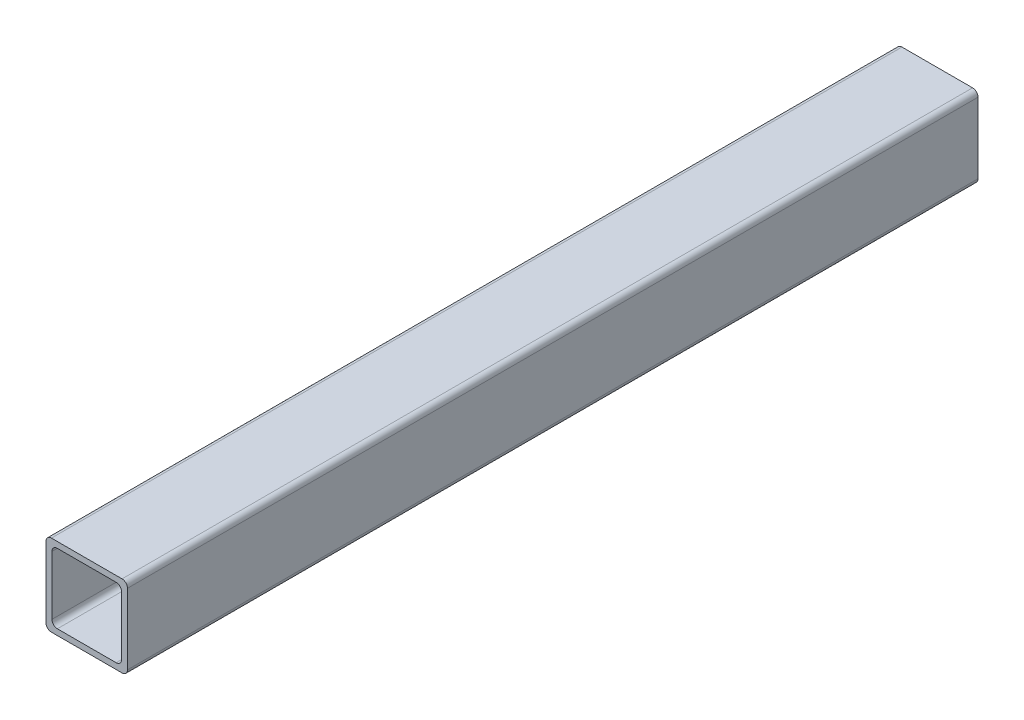
SolidWorks part; units mm, degrees
material "ASTM A500 Grade B Steel"
ref_plane "Front Plane" through (0, 0, 0) normal (0, 0, 1) x (1, 0, 0)
ref_plane "Top Plane" through (0, 0, 0) normal (0, 1, 0) x (1, 0, 0)
ref_plane "Right Plane" through (0, 0, 0) normal (1, 0, 0) x (0, 0, -1)
sketch "Sketch1" plane through (0, 0, 0) normal (0, 0, 1) x (1, 0, 0)
  line L0 (5.3086, -2.7686) -> (32.7914, -2.7686)
  line L1 (2.54, 0) -> (35.56, 0)
  line L2 (0, -2.54) -> (0, -35.56)
  line L3 (2.54, -38.1) -> (35.56, -38.1)
  line L4 (38.1, -2.54) -> (38.1, -35.56)
  line L5 (35.3314, -5.3086) -> (35.3314, -32.7914)
  line L6 (5.3086, -35.3314) -> (32.7914, -35.3314)
  line L7 (2.7686, -5.3086) -> (2.7686, -32.7914)
  line L8 (0, 0) -> (0, -38.1) construction
  line L9 (0, -38.1) -> (38.1, -38.1) construction
  line L10 (38.1, 0) -> (38.1, -38.1) construction
  line L11 (2.7686, -2.7686) -> (2.7686, -35.3314) construction
  line L12 (2.7686, -35.3314) -> (35.3314, -35.3314) construction
  line L13 (35.3314, -2.7686) -> (35.3314, -35.3314) construction
  line L14 (2.7686, -2.7686) -> (35.3314, -2.7686) construction
  line L15 (0, 0) -> (38.1, 0) construction
  arc A0 (0, -35.56) -> (2.54, -38.1) centre (2.54, -35.56) ccw
  arc A1 (38.1, -35.56) -> (35.56, -38.1) centre (35.56, -35.56) cw
  arc A2 (2.7686, -32.7914) -> (5.3086, -35.3314) centre (5.3086, -32.7914) ccw
  arc A3 (32.7914, -35.3314) -> (35.3314, -32.7914) centre (32.7914, -32.7914) ccw
  arc A4 (35.3314, -5.3086) -> (32.7914, -2.7686) centre (32.7914, -5.3086) ccw
  arc A5 (38.1, -2.54) -> (35.56, 0) centre (35.56, -2.54) ccw
  arc A6 (0, -2.54) -> (2.54, 0) centre (2.54, -2.54) cw
  arc A7 (5.3086, -2.7686) -> (2.7686, -5.3086) centre (5.3086, -5.3086) ccw
  point P12 (0, -38.1)
  dimension "D4" = 2.54
  dimension "D3" = 2.7686
extrude "Boss-Extrude1" add sketch "Sketch1" along normal blind 397
sketch "Sketch2" plane through (0, 0, 0) normal (0, 0, -1) x (-1, 0, 0)
  line L4 (0, -35.56) -> (0, -2.54)
  line L5 (-2.54, 0) -> (-35.56, 0)
  line L6 (-38.1, -2.54) -> (-38.1, -35.56)
  line L7 (-35.56, -38.1) -> (-2.54, -38.1)
  line L8 (0, -35.56) -> (0, -2.54)
  line L9 (-2.54, 0) -> (-35.56, 0)
  line L10 (-38.1, -2.54) -> (-38.1, -35.56)
  line L11 (-35.56, -38.1) -> (-2.54, -38.1)
  arc A4 (-2.54, -38.1) -> (0, -35.56) centre (-2.54, -35.56) ccw
  arc A5 (0, -2.54) -> (-2.54, 0) centre (-2.54, -2.54) ccw
  arc A6 (-35.56, 0) -> (-38.1, -2.54) centre (-35.56, -2.54) ccw
  arc A7 (-38.1, -35.56) -> (-35.56, -38.1) centre (-35.56, -35.56) ccw
  arc A8 (-2.54, -38.1) -> (0, -35.56) centre (-2.54, -35.56) ccw
  arc A9 (0, -2.54) -> (-2.54, 0) centre (-2.54, -2.54) ccw
  arc A10 (-35.56, 0) -> (-38.1, -2.54) centre (-35.56, -2.54) ccw
  arc A11 (-38.1, -35.56) -> (-35.56, -38.1) centre (-35.56, -35.56) ccw
  dimension "D1" = 0
extrude "Boss-Extrude2" add sketch "Sketch2" along normal up to surface (0.6787 mm away)
